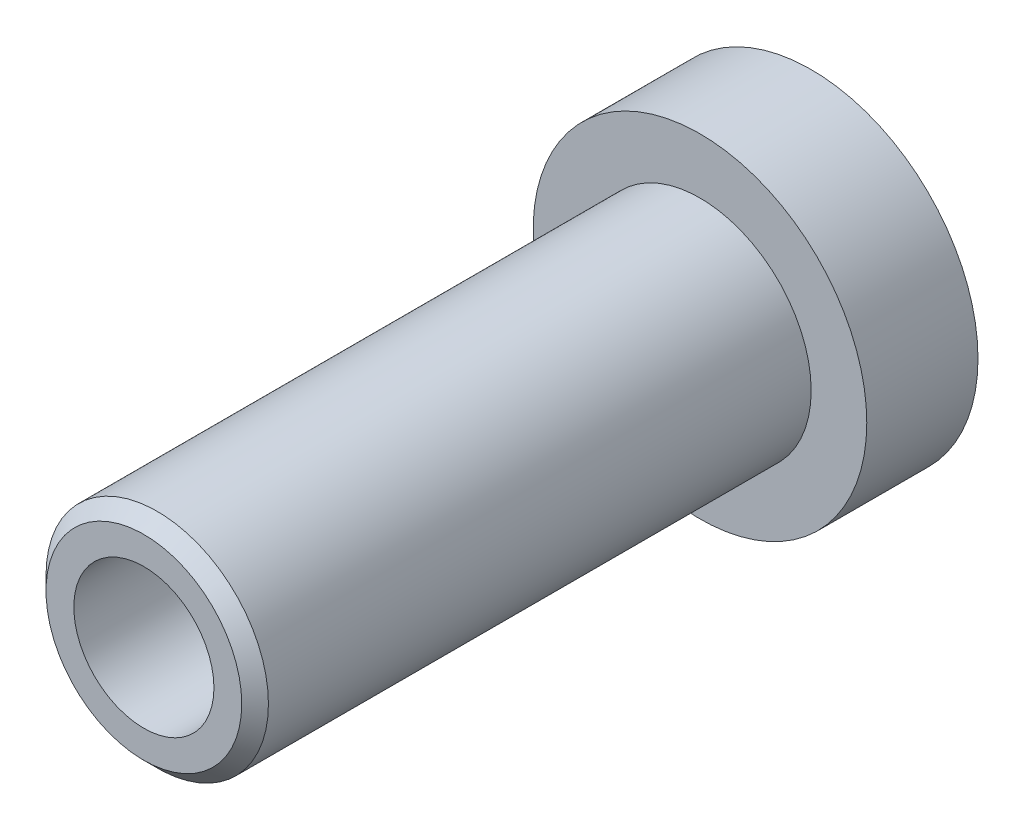
SolidWorks part; units mm, degrees
ref_plane "Front Plane" through (0, 0, 0) normal (0, 0, 1) x (1, 0, 0)
ref_plane "Top Plane" through (0, 0, 0) normal (0, 1, 0) x (1, 0, 0)
ref_plane "Right Plane" through (0, 0, 0) normal (1, 0, 0) x (0, 0, -1)
sketch "Sketch1" plane through (0, 0, 0) normal (0, 0, 1) x (1, 0, 0)
  circle A0 centre (0, 0) radius 0.75
  dimension "D1" = 1.5
extrude "Boss-Extrude1" add sketch "Sketch1" along normal blind 0.5
sketch "Sketch2" plane through (0, 0, 0.5) normal (0, 0, 1) x (1, 0, 0)
  circle A0 centre (0, 0) radius 0.5
  dimension "D1" = 1
extrude "Boss-Extrude2" add sketch "Sketch2" along normal blind 2.5
sketch "Sketch3" plane through (0, 0, 3) normal (0, 0, 1) x (1, 0, 0)
  circle A0 centre (0, 0) radius 0.315
  dimension "D1" = 0.63
extrude "Cut-Extrude1" cut sketch "Sketch3" against normal blind 3
sketch "Sketch5" plane through (0, 0, 0) normal (1, 0, 0) x (0, 0, -1)
  line L0 (-3, 0.5) -> (-2.94, 0.5)
  line L1 (-0.5, 0.5) -> (-3, 0.5) construction
  line L2 (-2.94, 0.5) -> (-3, 0.44)
  line L3 (-3, 0.5) -> (-3, -0.5) construction
  line L4 (-3, 0.44) -> (-3, 0.5)
  line L5 (-3, 0) -> (0, 0) construction
  line L6 (-1.5, 0) -> (-1.5, 0.5471) construction
  dimension "D1" = 0.06
  dimension "D2" = 0.06
revolve "Cut-Revolve1" cut sketch "Sketch5" angle 360 about L5
